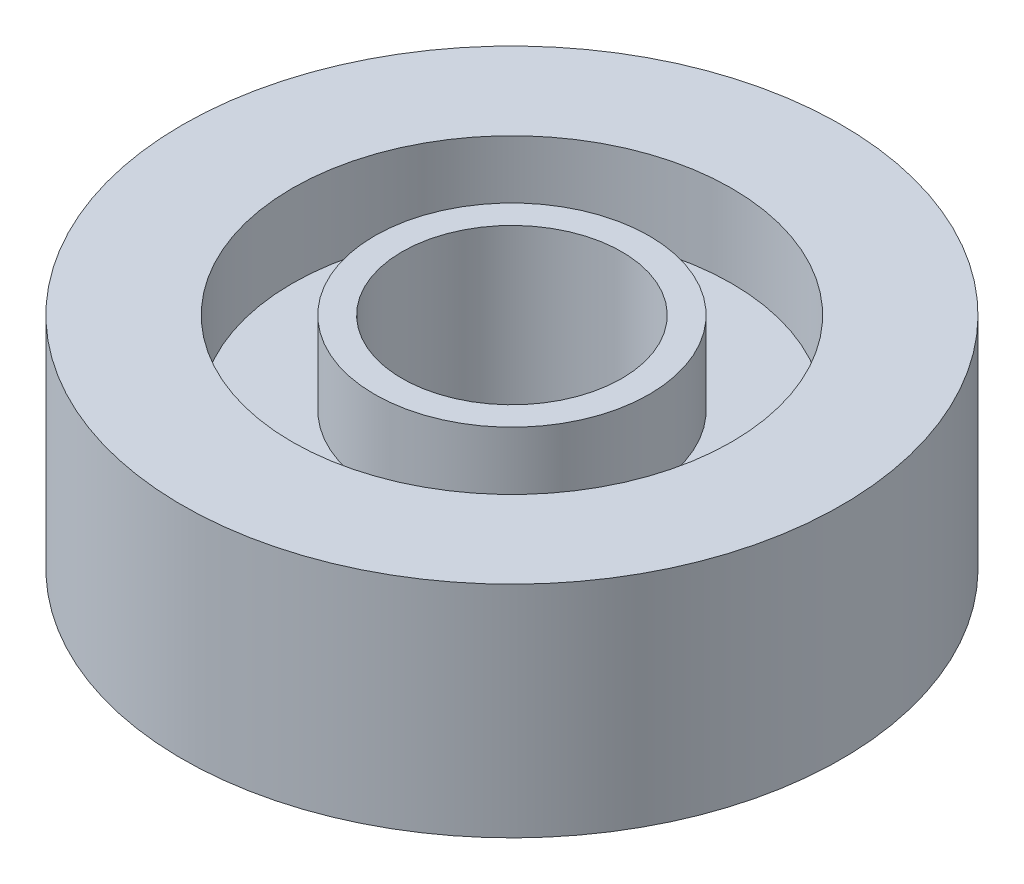
SolidWorks part; units mm, degrees
ref_plane "Front Plane" through (0, 0, 0) normal (0, 0, 1) x (1, 0, 0)
ref_plane "Top Plane" through (0, 0, 0) normal (0, 1, 0) x (1, 0, 0)
ref_plane "Right Plane" through (0, 0, 0) normal (1, 0, 0) x (0, 0, -1)
sketch "Sketch1" plane through (0, 0, 0) normal (0, 0, 1) x (1, 0, 0)
  line L0 (-2.8973, 6.3696) -> (-2.8973, -2.3389) construction
  line L2 (1.1027, -4) -> (2.1027, -4)
  line L3 (2.1027, -4) -> (2.1027, -1)
  line L4 (2.1027, 4) -> (1.1027, 4)
  line L5 (2.1027, 1) -> (5.1027, 1)
  line L6 (2.1027, -1) -> (5.1027, -1)
  line L9 (5.1027, 4) -> (5.1027, 1)
  line L11 (5.1027, -4) -> (5.1027, -1)
  line L12 (-3.3723, 0) -> (10.1415, 0) construction
  line L13 (1.1027, 4) -> (1.1027, -4)
  line L14 (2.1027, 1) -> (2.1027, 4)
  line L15 (5.1027, -4) -> (9.1027, -4)
  line L16 (9.1027, -4) -> (9.1027, 4)
  line L17 (9.1027, 4) -> (5.1027, 4)
  dimension "D1" = 4
  dimension "D2" = 12
  dimension "D3" = 8
  dimension "D4" = 1
  dimension "D5" = 1
  dimension "D6" = 3
  dimension "D7" = 4
  dimension "D8" = 1
revolve "Revolve1" add sketch "Sketch1" angle 360 about L0
